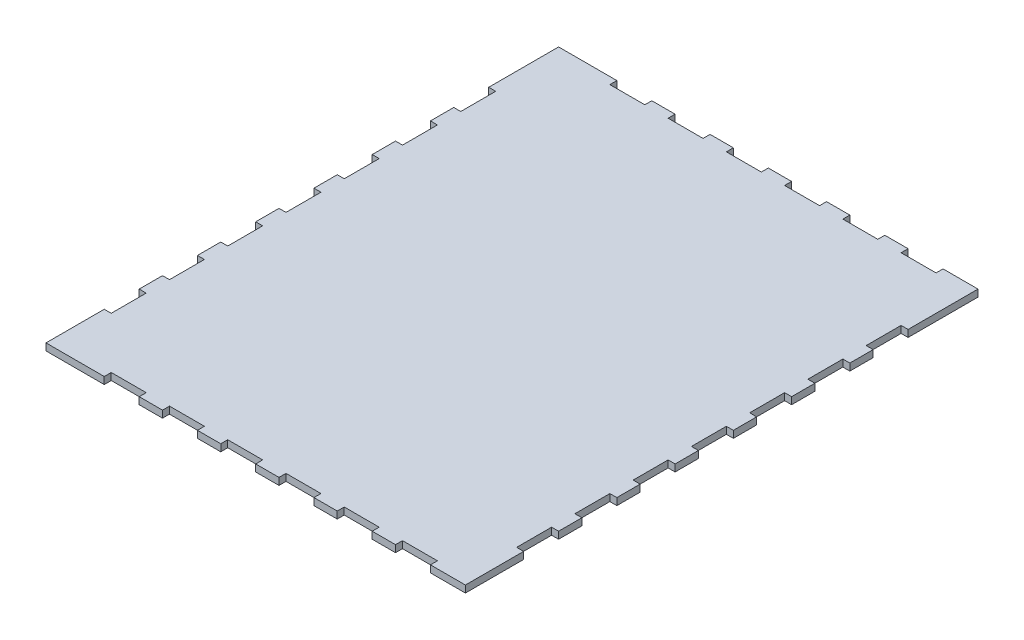
SolidWorks part; units mm, degrees
ref_plane "Front Plane" through (0, 0, 0) normal (0, 0, 1) x (1, 0, 0)
ref_plane "Top Plane" through (0, 0, 0) normal (0, 1, 0) x (1, 0, 0)
ref_plane "Right Plane" through (0, 0, 0) normal (1, 0, 0) x (0, 0, -1)
sketch "Sketch1" plane through (0, 0, 0) normal (0, 1, 0) x (1, 0, 0)
  line L0 (-90.3569, -190.1013) -> (-87.3569, -190.1013)
  line L1 (89.6431, -215.1013) -> (-90.3569, -215.1013)
  line L2 (89.6431, -215.1013) -> (89.6431, 4.8987)
  line L3 (89.6431, 4.8987) -> (-90.3569, 4.8987)
  line L4 (-90.3569, -215.1013) -> (-90.3569, 4.8987)
  line L5 (-87.3569, -190.1013) -> (-87.3569, -175.1013)
  line L6 (-87.3569, -175.1013) -> (-90.3569, -175.1013)
  line L7 (-87.3569, -150.1013) -> (-90.3569, -150.1013)
  line L8 (-87.3569, -165.1013) -> (-87.3569, -150.1013)
  line L9 (-90.3569, -165.1013) -> (-87.3569, -165.1013)
  line L10 (-87.3569, -125.1013) -> (-90.3569, -125.1013)
  line L11 (-87.3569, -140.1013) -> (-87.3569, -125.1013)
  line L12 (-90.3569, -140.1013) -> (-87.3569, -140.1013)
  line L13 (-87.3569, -100.1013) -> (-90.3569, -100.1013)
  line L14 (-87.3569, -115.1013) -> (-87.3569, -100.1013)
  line L15 (-90.3569, -115.1013) -> (-87.3569, -115.1013)
  line L16 (-87.3569, -75.1013) -> (-90.3569, -75.1013)
  line L17 (-87.3569, -90.1013) -> (-87.3569, -75.1013)
  line L18 (-90.3569, -90.1013) -> (-87.3569, -90.1013)
  line L19 (-87.3569, -50.1013) -> (-90.3569, -50.1013)
  line L20 (-87.3569, -65.1013) -> (-87.3569, -50.1013)
  line L21 (-90.3569, -65.1013) -> (-87.3569, -65.1013)
  line L22 (-87.3569, -25.1013) -> (-90.3569, -25.1013)
  line L23 (-87.3569, -40.1013) -> (-87.3569, -25.1013)
  line L24 (-90.3569, -40.1013) -> (-87.3569, -40.1013)
  line L25 (-65.3569, -215.1013) -> (-65.3569, -212.1013)
  line L26 (-65.3569, -212.1013) -> (-50.3569, -212.1013)
  line L27 (-50.3569, -212.1013) -> (-50.3569, -215.1013)
  line L28 (-40.3569, -212.1013) -> (-25.3569, -212.1013)
  line L29 (-25.3569, -212.1013) -> (-25.3569, -215.1013)
  line L30 (-40.3569, -215.1013) -> (-40.3569, -212.1013)
  line L31 (-15.3569, -212.1013) -> (-0.3569, -212.1013)
  line L32 (-0.3569, -212.1013) -> (-0.3569, -215.1013)
  line L33 (-15.3569, -215.1013) -> (-15.3569, -212.1013)
  line L34 (9.6431, -212.1013) -> (24.6431, -212.1013)
  line L35 (24.6431, -212.1013) -> (24.6431, -215.1013)
  line L36 (9.6431, -215.1013) -> (9.6431, -212.1013)
  line L37 (34.6431, -212.1013) -> (49.6431, -212.1013)
  line L38 (49.6431, -212.1013) -> (49.6431, -215.1013)
  line L39 (34.6431, -215.1013) -> (34.6431, -212.1013)
  line L40 (59.6431, -212.1013) -> (74.6431, -212.1013)
  line L41 (74.6431, -212.1013) -> (74.6431, -215.1013)
  line L42 (59.6431, -215.1013) -> (59.6431, -212.1013)
  line L43 (89.6431, -105.1013) -> (-90.3569, -105.1013) construction
  line L44 (-90.3569, -105.1013) -> (-0.3569, 4.8987) construction
  line L45 (-0.3569, 4.8987) -> (-0.3569, -215.1013) construction
  line L46 (89.6431, -40.1013) -> (86.6431, -40.1013)
  line L47 (86.6431, -40.1013) -> (86.6431, -25.1013)
  line L48 (86.6431, -25.1013) -> (89.6431, -25.1013)
  line L49 (89.6431, -65.1013) -> (86.6431, -65.1013)
  line L50 (86.6431, -65.1013) -> (86.6431, -50.1013)
  line L51 (86.6431, -50.1013) -> (89.6431, -50.1013)
  line L52 (89.6431, -90.1013) -> (86.6431, -90.1013)
  line L53 (86.6431, -90.1013) -> (86.6431, -75.1013)
  line L54 (86.6431, -75.1013) -> (89.6431, -75.1013)
  line L55 (89.6431, -115.1013) -> (86.6431, -115.1013)
  line L56 (86.6431, -115.1013) -> (86.6431, -100.1013)
  line L57 (86.6431, -100.1013) -> (89.6431, -100.1013)
  line L58 (89.6431, -140.1013) -> (86.6431, -140.1013)
  line L59 (86.6431, -140.1013) -> (86.6431, -125.1013)
  line L60 (86.6431, -125.1013) -> (89.6431, -125.1013)
  line L61 (89.6431, -165.1013) -> (86.6431, -165.1013)
  line L62 (86.6431, -165.1013) -> (86.6431, -150.1013)
  line L63 (86.6431, -150.1013) -> (89.6431, -150.1013)
  line L64 (86.6431, -175.1013) -> (89.6431, -175.1013)
  line L65 (86.6431, -190.1013) -> (86.6431, -175.1013)
  line L66 (89.6431, -190.1013) -> (86.6431, -190.1013)
  line L67 (59.6431, 4.8987) -> (59.6431, 1.8987)
  line L68 (74.6431, 1.8987) -> (74.6431, 4.8987)
  line L69 (59.6431, 1.8987) -> (74.6431, 1.8987)
  line L70 (34.6431, 4.8987) -> (34.6431, 1.8987)
  line L71 (49.6431, 1.8987) -> (49.6431, 4.8987)
  line L72 (34.6431, 1.8987) -> (49.6431, 1.8987)
  line L73 (9.6431, 4.8987) -> (9.6431, 1.8987)
  line L74 (24.6431, 1.8987) -> (24.6431, 4.8987)
  line L75 (9.6431, 1.8987) -> (24.6431, 1.8987)
  line L76 (-15.3569, 4.8987) -> (-15.3569, 1.8987)
  line L77 (-0.3569, 1.8987) -> (-0.3569, 4.8987)
  line L78 (-15.3569, 1.8987) -> (-0.3569, 1.8987)
  line L79 (-40.3569, 4.8987) -> (-40.3569, 1.8987)
  line L80 (-25.3569, 1.8987) -> (-25.3569, 4.8987)
  line L81 (-40.3569, 1.8987) -> (-25.3569, 1.8987)
  line L82 (-50.3569, 1.8987) -> (-50.3569, 4.8987)
  line L83 (-65.3569, 1.8987) -> (-50.3569, 1.8987)
  line L84 (-65.3569, 4.8987) -> (-65.3569, 1.8987)
  line L85 (89.6431, 4.8987) -> (-90.3569, 4.8987)
  dimension "D1" = 180
  dimension "D2" = 220
  dimension "D3" = 3
  dimension "D4" = 15
  dimension "D5" = 25
  dimension "D7" = 15
  dimension "D8" = 3
  dimension "D9" = 180
  dimension "D10" = 220
  dimension "D11" = 25
  dimension "D6" = 7
  dimension "D12" = 6
extrude "Boss-Extrude1" add sketch "Sketch1" along normal blind 3 contours L84 L3 L4 L22 L23 L24 L19 L20 L21 L16 L17 L18 L13 L14 L15 L10 L11 L12 L7 L8 L9 L6 L5 L0 L1 L25 L26 L27 L30 L28 L29 L33 L31 L32 L36 L34 L35 L39 L37 L38
